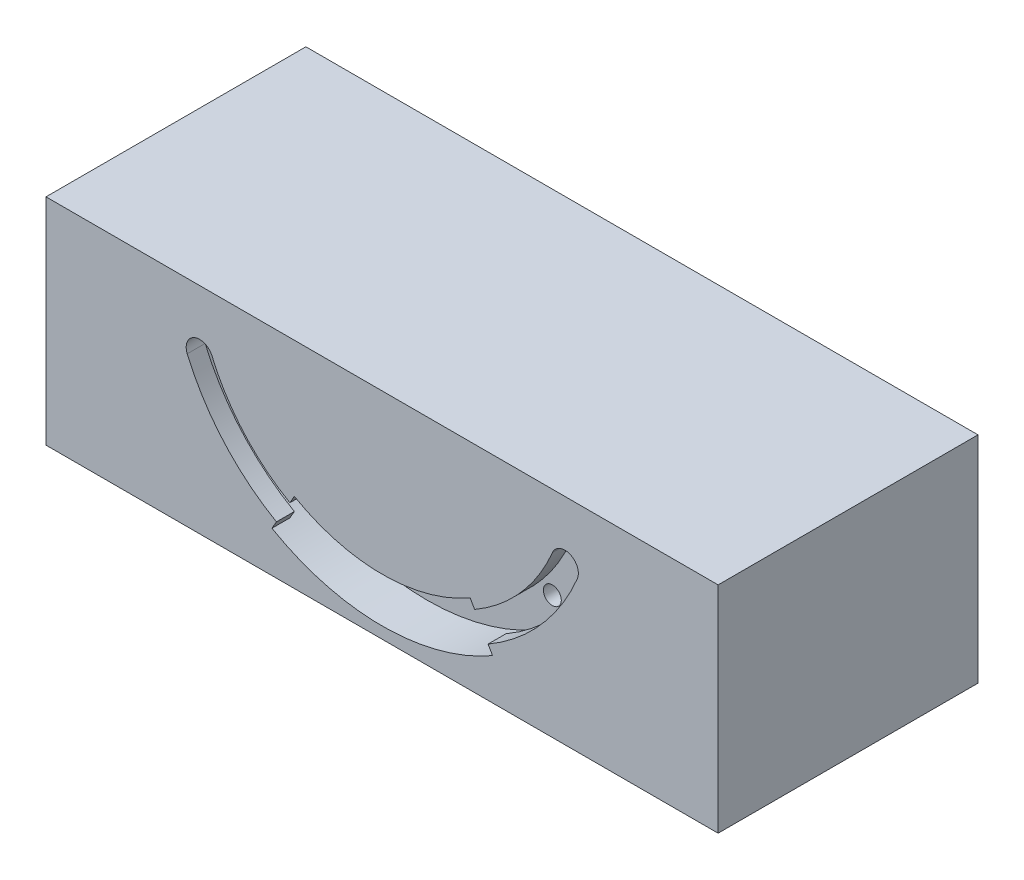
SolidWorks part; units mm, degrees
ref_plane "Front Plane" through (0, 0, 0) normal (0, 0, 1) x (1, 0, 0)
ref_plane "Top Plane" through (0, 0, 0) normal (0, 1, 0) x (1, 0, 0)
ref_plane "Right Plane" through (0, 0, 0) normal (1, 0, 0) x (0, 0, -1)
sketch "Sketch1" plane through (0, 0, 0) normal (0, 0, 1) x (1, 0, 0)
  line L1 (-23.625, 20.1562) -> (51.375, 20.1562)
  line L2 (-23.625, 20.1562) -> (-23.625, -3.8438)
  line L3 (-23.625, -3.8438) -> (51.375, -3.8438)
  line L4 (51.375, 20.1562) -> (51.375, -3.8438)
  dimension "D1" = 75
  dimension "D2" = 24
extrude "Boss-Extrude1" add sketch "Sketch1" along normal blind 24 and the other way blind 3
sketch "Sketch2" plane through (0, 0, 24) normal (0, 0, 1) x (1, 0, 0)
  line L0 (51.375, 20.1562) -> (-23.625, 20.1562) construction
  line L1 (-18.625, 18.1562) -> (11.375, 18.1562)
  line L2 (-18.625, 18.1562) -> (-18.625, -1.8438)
  line L3 (-18.625, -1.8438) -> (11.375, -1.8438)
  line L4 (11.375, 18.1562) -> (11.375, -1.8438)
  line L5 (16.375, 18.1562) -> (46.375, 18.1562)
  line L6 (16.375, 18.1562) -> (16.375, -1.8438)
  line L7 (16.375, -1.8438) -> (46.375, -1.8438)
  line L8 (46.375, 18.1562) -> (46.375, -1.8438)
  line L9 (-23.625, -3.8438) -> (51.375, -3.8438) construction
  line L10 (-23.625, 20.1562) -> (-23.625, -3.8438) construction
  line L11 (51.375, -3.8438) -> (51.375, 20.1562) construction
  dimension "D1" = 2
  dimension "D2" = 2
  dimension "D3" = 5
  dimension "D4" = 30
  dimension "D5" = 30
  dimension "D6" = 5
  dimension "D7" = 2
  dimension "D8" = 2
extrude "Cut-Extrude1" cut sketch "Sketch2" against normal blind 20 from offset 5 offset against normal yes
sketch "Sketch3" plane through (0, 0, 24) normal (0, 0, 1) x (1, 0, 0)
  arc A5 (34.2787, 13.464) -> (-6.481, 13.4536) centre (13.8967, 22.0549) cw construction
  arc A6 (-8.7842, 12.4815) -> (36.5825, 12.493) centre (13.8967, 22.0549) ccw
  arc A7 (-4.1778, 14.4258) -> (31.975, 14.435) centre (13.8967, 22.0549) ccw
  arc A8 (-4.1778, 14.4258) -> (-8.7842, 12.4815) centre (-6.481, 13.4536) ccw
  arc A9 (36.5825, 12.493) -> (31.975, 14.435) centre (34.2787, 13.464) ccw
  point P8 (13.9023, -0.0637)
extrude "Cut-Extrude2" cut sketch "Sketch3" against normal blind 3
sketch "Sketch20" plane through (0, 0, 24) normal (0, 0, 1) x (1, 0, 0)
  line L0 (51.375, 20.1562) -> (-23.625, 20.1562) construction
  circle A1 centre (27.875, 4.9062) radius 1
  circle A2 centre (-0.125, 4.9062) radius 1
  arc A3 (-4.1778, 14.4258) -> (31.975, 14.435) centre (13.8967, 22.0549) ccw construction
  arc A4 (-4.1778, 14.4258) -> (31.975, 14.435) centre (13.8967, 22.0549) ccw construction
  point P8 (27.875, 5.3022)
  point P9 (-0.125, 5.3022)
  point P12 (-0.125, 4.8176)
  point P13 (0, 0)
  point P14 (-0.125, 4.8996)
  point P15 (27.875, 4.9816)
  dimension "D1" = 14.0217
  dimension "D3" = 15.25
  dimension "D2" = 13.9783
  dimension "D4" = 15.25
extrude "Cut-Extrude3" cut sketch "Sketch20" against normal up to next
sketch "Sketch21" plane through (0, 0, -3) normal (0, 0, -1) x (-1, 0, 0)
  circle A0 centre (-32.6802, 5.0759) radius 1.5
  circle A1 centre (-27.8617, 5.0878) radius 1.5
  circle A2 centre (0.1117, 5.0878) radius 1.5
  circle A3 centre (4.9302, 5.0759) radius 1.5
extrude "Cut-Extrude4" cut sketch "Sketch21" against normal up to next
sketch "Sketch24" plane through (0, 0, 24) normal (0, 0, 1) x (1, 0, 0)
  line L0 (13.8967, 22.0549) -> (13.8967, -14.2384) construction
  line L4 (-23.625, 20.1562) -> (-23.625, -3.8438)
  line L5 (-23.625, -3.8438) -> (51.375, -3.8438)
  line L6 (51.375, -3.8438) -> (51.375, 20.1562)
  line L7 (51.375, 20.1562) -> (-23.625, 20.1562)
  line L8 (-23.625, 20.1562) -> (-23.625, -3.8438)
  line L9 (-23.625, -3.8438) -> (51.375, -3.8438)
  line L10 (51.375, -3.8438) -> (51.375, 20.1562)
  line L11 (51.375, 20.1562) -> (-23.625, 20.1562)
  arc A8 (-7.8629, 12.8703) -> (35.661, 12.8814) centre (13.8967, 22.0549) ccw
  arc A9 (35.661, 12.8814) -> (32.8965, 14.0466) centre (34.2787, 13.464) ccw
  arc A10 (-5.099, 14.0369) -> (32.8965, 14.0466) centre (13.8967, 22.0549) ccw
  arc A11 (-5.099, 14.0369) -> (-7.8629, 12.8703) centre (-6.481, 13.4536) ccw
  arc A12 (-7.8629, 12.8703) -> (35.661, 12.8814) centre (13.8967, 22.0549) ccw
  arc A13 (35.661, 12.8814) -> (32.8965, 14.0466) centre (34.2787, 13.464) ccw
  arc A14 (-5.099, 14.0369) -> (32.8965, 14.0466) centre (13.8967, 22.0549) ccw
  arc A15 (-5.099, 14.0369) -> (-7.8629, 12.8703) centre (-6.481, 13.4536) ccw
  dimension "D1" = 1
  dimension "D2" = 0
extrude "Boss-Extrude2" add sketch "Sketch24" along normal blind 2
sketch "Sketch26" plane through (0, 0, 26) normal (0, 0, 1) x (1, 0, 0)
  line L0 (13.8967, 22.0549) -> (13.8967, -9.7833) construction
  line L1 (23.706, 5.0647) -> (26.206, 0.7346)
  line L2 (4.0874, 5.0647) -> (1.5874, 0.7346)
  line L3 (23.706, 5.0647) -> (13.8967, 22.0549) construction
  line L4 (13.8967, 22.0549) -> (4.0874, 5.0647) construction
  arc A0 (-8.7842, 12.4815) -> (36.5825, 12.493) centre (13.8967, 22.0549) ccw construction
  arc A5 (-8.7842, 12.4815) -> (36.5825, 12.493) centre (13.8967, 22.0549) ccw
  arc A6 (36.5825, 12.493) -> (31.975, 14.435) centre (34.2787, 13.464) ccw
  arc A7 (-4.1778, 14.4258) -> (31.975, 14.435) centre (13.8967, 22.0549) ccw
  arc A8 (-4.1778, 14.4258) -> (-8.7842, 12.4815) centre (-6.481, 13.4536) ccw
  arc A9 (1.5874, 0.7346) -> (26.206, 0.7346) centre (13.8967, 22.0549) ccw
  arc A11 (4.0874, 5.0647) -> (23.706, 5.0647) centre (13.8967, 22.0549) ccw
  dimension "D2" = 60
  dimension "D1" = 0
extrude "Cut-Extrude5" cut sketch "Sketch26" against normal up to surface (5 mm away) up to face at (28.875, 4.9062, 21)
